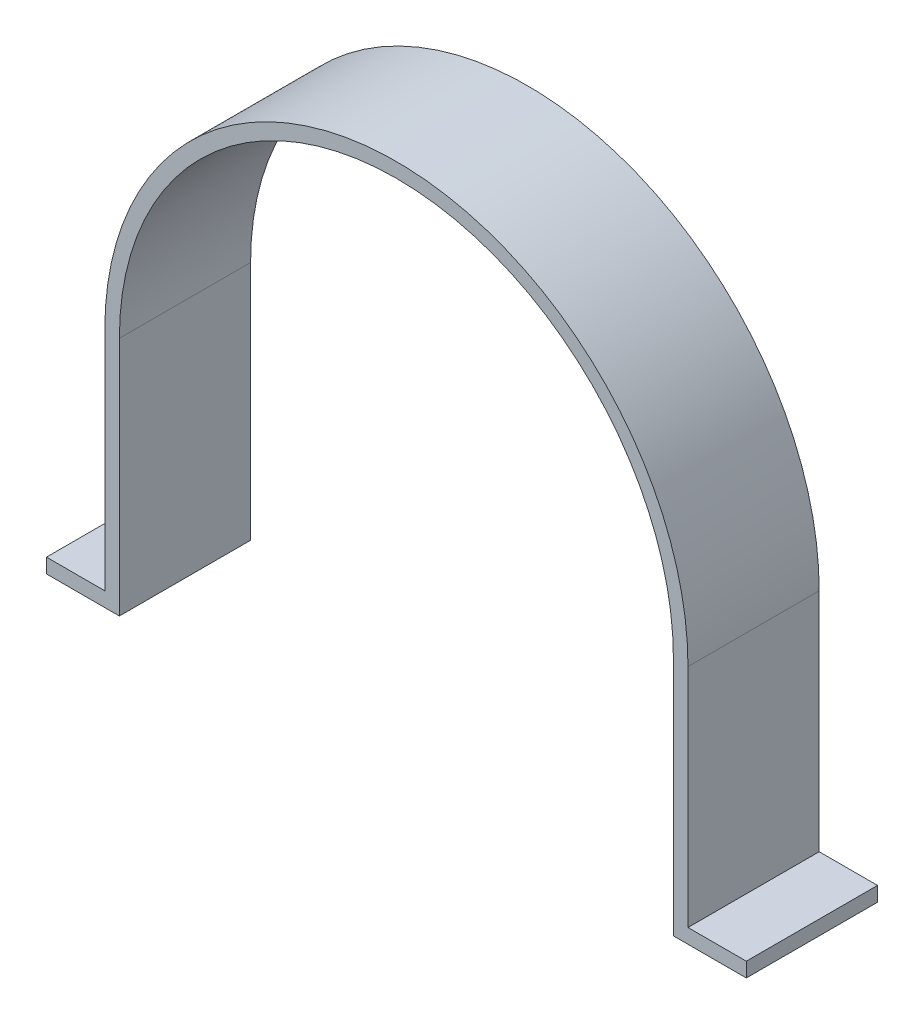
SolidWorks part; units mm, degrees
ref_plane "Front Plane" through (0, 0, 0) normal (0, 0, 1) x (1, 0, 0)
ref_plane "Top Plane" through (0, 0, 0) normal (0, 1, 0) x (1, 0, 0)
ref_plane "Right Plane" through (0, 0, 0) normal (1, 0, 0) x (0, 0, -1)
sketch "Band cross-section profile" plane through (0, 0, 0) normal (0, 0, 1) x (1, 0, 0)
  line L0 (19, 28.5) -> (19, 12)
  line L1 (19, 12) -> (24, 12)
  line L2 (24, 12) -> (24, 13)
  line L3 (24, 13) -> (20, 13)
  line L4 (20, 13) -> (20, 28.5)
  line L5 (-20, 28.5) -> (-20, 13)
  line L6 (-20, 13) -> (-24, 13)
  line L7 (-24, 13) -> (-24, 12)
  line L8 (-24, 12) -> (-19, 12)
  line L9 (-19, 12) -> (-19, 28.5)
  arc A0 (-19, 28.5) -> (19, 28.5) centre (0, 28.5) cw
  arc A1 (20, 28.5) -> (-20, 28.5) centre (0, 28.5) ccw
extrude "Band cross-section" add sketch "Band cross-section profile" along normal blind 9
